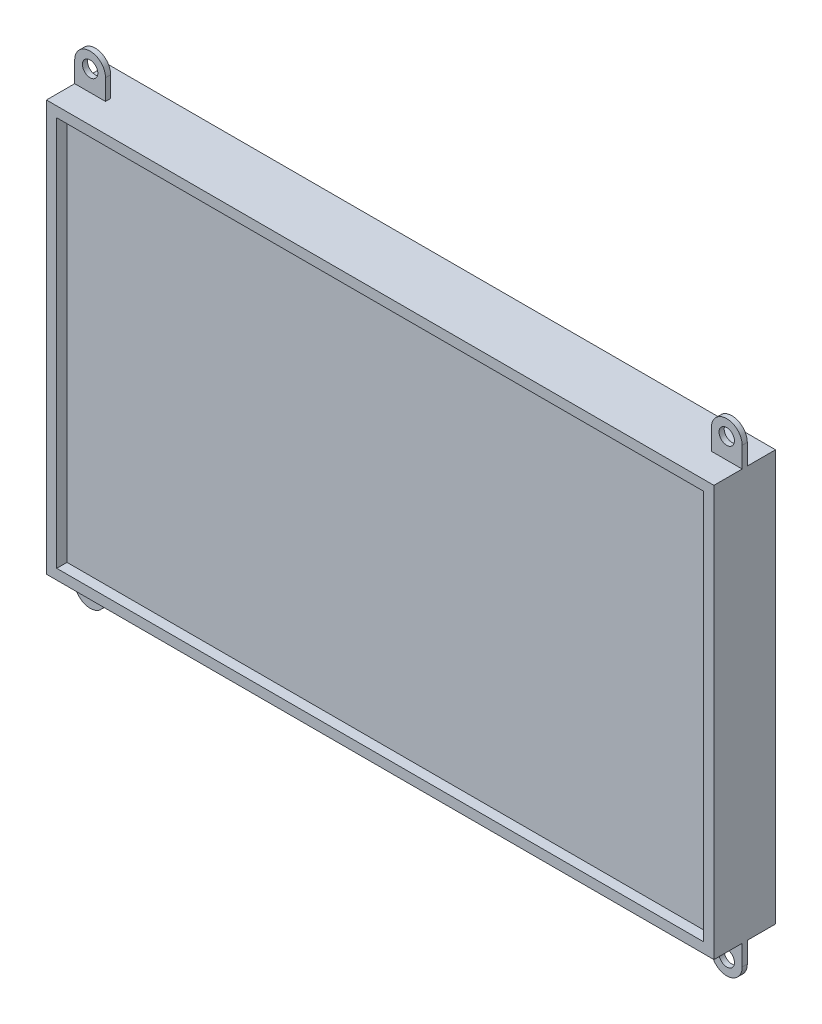
SolidWorks part; units mm, degrees
ref_plane "Front Plane" through (0, 0, 0) normal (0, 0, 1) x (1, 0, 0)
ref_plane "Top Plane" through (0, 0, 0) normal (0, 1, 0) x (1, 0, 0)
ref_plane "Right Plane" through (0, 0, 0) normal (1, 0, 0) x (0, 0, -1)
sketch "Sketch1" plane through (0, 0, 0) normal (0, 0, 1) x (1, 0, 0)
  line L1 (-82.55, 50.8) -> (82.55, 50.8)
  line L2 (-82.55, 50.8) -> (-82.55, -50.8)
  line L3 (-82.55, -50.8) -> (82.55, -50.8)
  line L4 (82.55, 50.8) -> (82.55, -50.8)
  line L5 (-82.55, 50.8) -> (82.55, -50.8) construction
  line L6 (-82.55, -50.8) -> (82.55, 50.8) construction
  point P0 (0, 0)
  dimension "D1" = 101.6
  dimension "D2" = 165.1
extrude "Boss-Extrude1" add sketch "Sketch1" along normal mid plane 15.24
sketch "Sketch2" plane through (0, 0, 7.62) normal (0, 0, 1) x (1, 0, 0)
  line L0 (82.55, 50.8) -> (-82.55, 50.8) construction
  line L1 (-80.01, 48.26) -> (80.01, 48.26)
  line L2 (-80.01, 48.26) -> (-80.01, -48.26)
  line L3 (-80.01, -48.26) -> (80.01, -48.26)
  line L4 (80.01, 48.26) -> (80.01, -48.26)
  line L5 (-80.01, 48.26) -> (80.01, -48.26) construction
  line L6 (-80.01, -48.26) -> (80.01, 48.26) construction
  line L7 (-82.55, 50.8) -> (-82.55, -50.8) construction
  point P0 (0, 0)
  dimension "D1" = 2.54
  dimension "D2" = 2.54
extrude "Cut-Extrude1" cut sketch "Sketch2" against normal blind 2.54
sketch "Sketch3" plane through (0, 0, -7.62) normal (0, 0, -1) x (-1, 0, 0)
  line L0 (-82.55, 55.88) -> (-82.55, 50.8)
  line L1 (-82.55, 55.88) -> (-74.93, 55.88) construction
  line L2 (-74.93, 55.88) -> (-74.93, 50.8)
  line L3 (-82.55, 50.8) -> (82.55, 50.8) construction
  line L4 (-82.55, 50.8) -> (-74.93, 50.8)
  arc A0 (-82.55, 55.88) -> (-74.93, 55.88) centre (-78.74, 55.88) cw
  dimension "D1" = 7.62
  dimension "D2" = 5.08
extrude "Boss-Extrude2" add sketch "Sketch3" against normal mid plane 1.27 from offset 7.62 offset against normal yes
sketch "Sketch4" plane through (0, 0, 0.635) normal (0, 0, 1) x (1, 0, 0)
  circle A0 centre (78.74, 55.88) radius 1.905
  dimension "D1" = 3.81
extrude "Cut-Extrude2" cut sketch "Sketch4" against normal through all
mirror "Mirror1" about plane through (0, 0, 0) normal (0, 1, 0) of "Cut-Extrude2", "Boss-Extrude2"
mirror "Mirror2" about plane through (0, 0, 0) normal (1, 0, 0) of "Mirror1", "Boss-Extrude2", "Cut-Extrude2"
